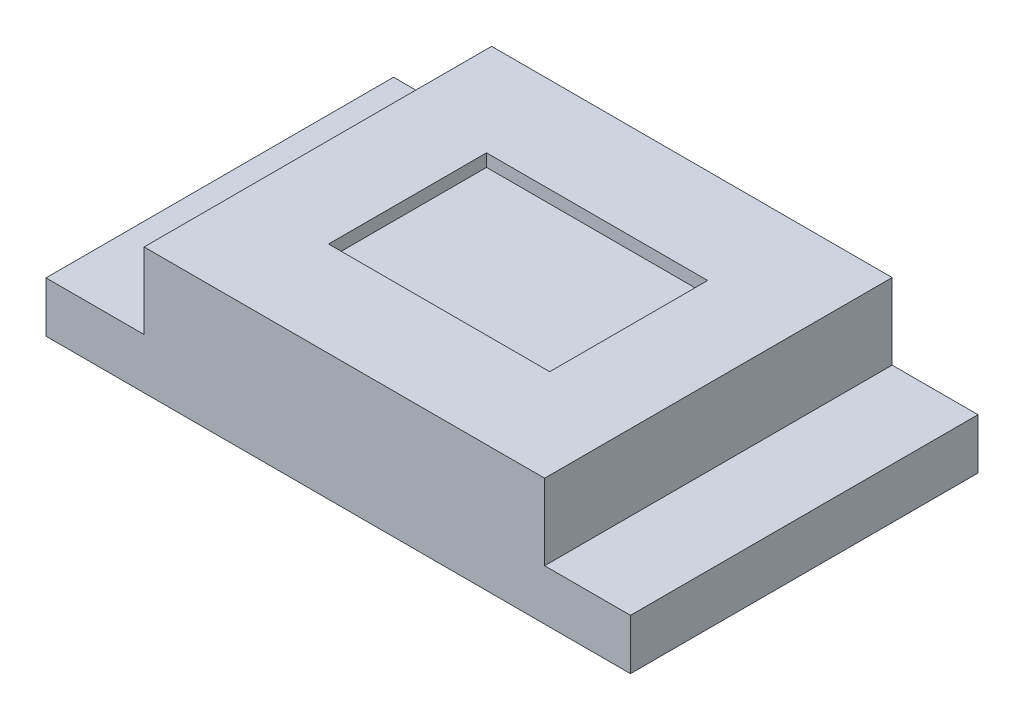
SolidWorks part; units mm, degrees
ref_plane "Front Plane" through (0, 0, 0) normal (0, 0, 1) x (1, 0, 0)
ref_plane "Top Plane" through (0, 0, 0) normal (0, 1, 0) x (1, 0, 0)
ref_plane "Right Plane" through (0, 0, 0) normal (1, 0, 0) x (0, 0, -1)
sketch "Sketch1" plane through (0, 0, 0) normal (0, 1, 0) x (1, 0, 0)
  line L1 (0, 0) -> (117.475, 0)
  line L2 (0, 0) -> (0, 69.85)
  line L3 (0, 69.85) -> (117.475, 69.85)
  line L4 (117.475, 0) -> (117.475, 69.85)
  dimension "D1" = 117.475
  dimension "D2" = 69.85
extrude "Boss-Extrude1" add sketch "Sketch1" along normal blind 25.4
sketch "Sketch2" plane through (0, 25.4, 0) normal (0, 1, 0) x (1, 0, 0)
  line L0 (19.7162, 69.85) -> (19.7162, 0)
  line L1 (117.475, 69.85) -> (0, 69.85) construction
  line L2 (0, 0) -> (117.475, 0) construction
  line L3 (19.7162, 0) -> (100.2182, 0)
  line L4 (100.2182, 0) -> (100.2182, 69.85)
  line L5 (117.475, 0) -> (117.475, 69.85) construction
  line L6 (0, 69.85) -> (0, 0) construction
  line L7 (117.475, 0) -> (117.475, 69.85)
  line L8 (117.475, 69.85) -> (0, 69.85)
  line L9 (0, 0) -> (117.475, 0)
  line L10 (0, 69.85) -> (0, 0)
  line M1 (0, 69.85) -> (0, 0)
  line M2 (0, 0) -> (117.475, 0)
  line M3 (117.475, 0) -> (117.475, 69.85)
  line M4 (117.475, 69.85) -> (0, 69.85)
extrude "Cut-Extrude2" cut sketch "Sketch2" against normal blind 15.24 contours L0 M4 M1 M2 | L4 M2 M3 M4
sketch "Sketch3" plane through (0, 25.4, 0) normal (0, 1, 0) x (1, 0, 0)
  line L0 (100.2182, 69.85) -> (19.7162, 69.85) construction
  line L1 (100.2182, 0) -> (100.2182, 69.85) construction
  line L2 (19.7162, 0) -> (100.2182, 0) construction
  line L3 (19.7162, 69.85) -> (19.7162, 0) construction
  line L4 (100.2182, 69.85) -> (19.7162, 69.85)
  line L5 (100.2182, 0) -> (100.2182, 69.85)
  line L6 (19.7162, 0) -> (100.2182, 0)
  line L7 (19.7162, 69.85) -> (19.7162, 0)
  line L8 (59.9672, 69.85) -> (59.9672, 0) construction
  line L10 (37.7422, 19.05) -> (82.1922, 19.05)
  line L11 (37.7422, 19.05) -> (37.7422, 50.8)
  line L12 (37.7422, 50.8) -> (82.1922, 50.8)
  line L13 (82.1922, 19.05) -> (82.1922, 50.8)
  line L14 (37.7422, 19.05) -> (82.1922, 50.8) construction
  line L15 (37.7422, 50.8) -> (82.1922, 19.05) construction
  point P6 (59.9672, 34.925)
  dimension "D1" = 44.45
  dimension "D2" = 31.75
extrude "Cut-Extrude4" cut sketch "Sketch3" against normal blind 2.54 contours L10 L13 L12 L11
